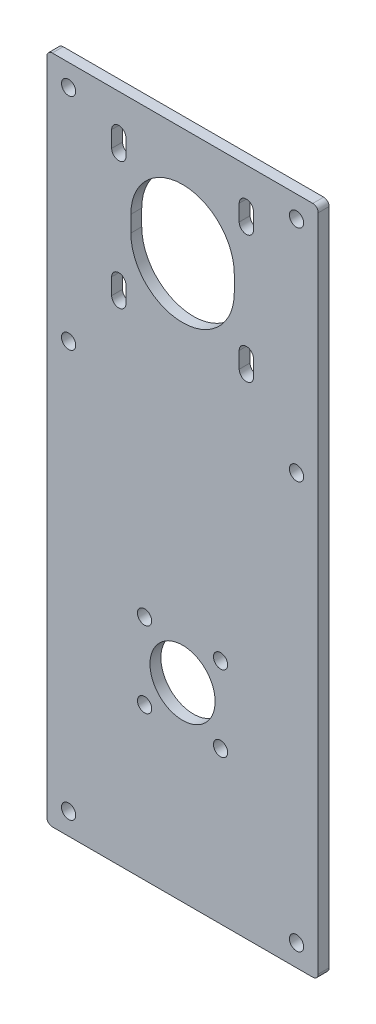
SolidWorks part; units mm, degrees
ref_plane "Front Plane" through (0, 0, 0) normal (0, 0, 1) x (1, 0, 0)
ref_plane "Top Plane" through (0, 0, 0) normal (0, 1, 0) x (1, 0, 0)
ref_plane "Right Plane" through (0, 0, 0) normal (1, 0, 0) x (0, 0, -1)
ref_plane "Plane1" through (0, 0, 4) normal (0, 0, 1) x (1, 0, 0)
sketch "Sketch1" plane through (0, 0, 4) normal (0, 0, 1) x (1, 0, 0)
  line L0 (-26.13, 57) -> (-26.13, 63)
  line L1 (-20.87, 63) -> (-20.87, 57)
  line L2 (20.87, 104) -> (20.87, 110)
  line L3 (26.13, 110) -> (26.13, 104)
  line L4 (-19.05, 80.5) -> (-19.05, 86.5)
  line L5 (19.05, 86.5) -> (19.05, 80.5)
  line L6 (26.13, 63) -> (26.13, 57)
  line L7 (20.87, 57) -> (20.87, 63)
  line L8 (-20.87, 110) -> (-20.87, 104)
  line L9 (-26.13, 104) -> (-26.13, 110)
  line L10 (-48, -123.5) -> (48, -123.5)
  line L11 (50, -121.5) -> (50, 121.5)
  line L12 (48, 123.5) -> (-48, 123.5)
  line L13 (-50, 121.5) -> (-50, -121.5)
  circle A0 centre (14, -67.5) radius 2.625
  circle A1 centre (-14, -67.5) radius 2.625
  circle A2 centre (14, -39.5) radius 2.625
  arc A3 (-20.87, 57) -> (-26.13, 57) centre (-23.5, 57) cw
  arc A4 (-26.13, 63) -> (-20.87, 63) centre (-23.5, 63) cw
  circle A5 centre (42, 115.5) radius 2.625
  circle A6 centre (0, -53.5) radius 12
  arc A7 (26.13, 104) -> (20.87, 104) centre (23.5, 104) cw
  arc A8 (20.87, 110) -> (26.13, 110) centre (23.5, 110) cw
  arc A9 (19.05, 80.5) -> (-19.05, 80.5) centre (0, 80.5) cw
  arc A10 (-19.05, 86.5) -> (19.05, 86.5) centre (0, 86.5) cw
  arc A11 (20.87, 63) -> (26.13, 63) centre (23.5, 63) cw
  arc A12 (26.13, 57) -> (20.87, 57) centre (23.5, 57) cw
  circle A13 centre (-42, 34.5) radius 2.625
  circle A14 centre (-42, -115.5) radius 2.625
  circle A15 centre (-14, -39.5) radius 2.625
  circle A16 centre (42, 34.5) radius 2.625
  circle A17 centre (42, -115.5) radius 2.625
  circle A18 centre (-42, 115.5) radius 2.625
  arc A19 (-26.13, 110) -> (-20.87, 110) centre (-23.5, 110) cw
  arc A20 (-20.87, 104) -> (-26.13, 104) centre (-23.5, 104) cw
  arc A21 (-50, -121.5) -> (-48, -123.5) centre (-48, -121.5) ccw
  arc A22 (48, -123.5) -> (50, -121.5) centre (48, -121.5) ccw
  arc A23 (50, 121.5) -> (48, 123.5) centre (48, 121.5) ccw
  arc A24 (-48, 123.5) -> (-50, 121.5) centre (-48, 121.5) ccw
extrude "Boss-Extrude1" add sketch "Sketch1" against normal blind 4
